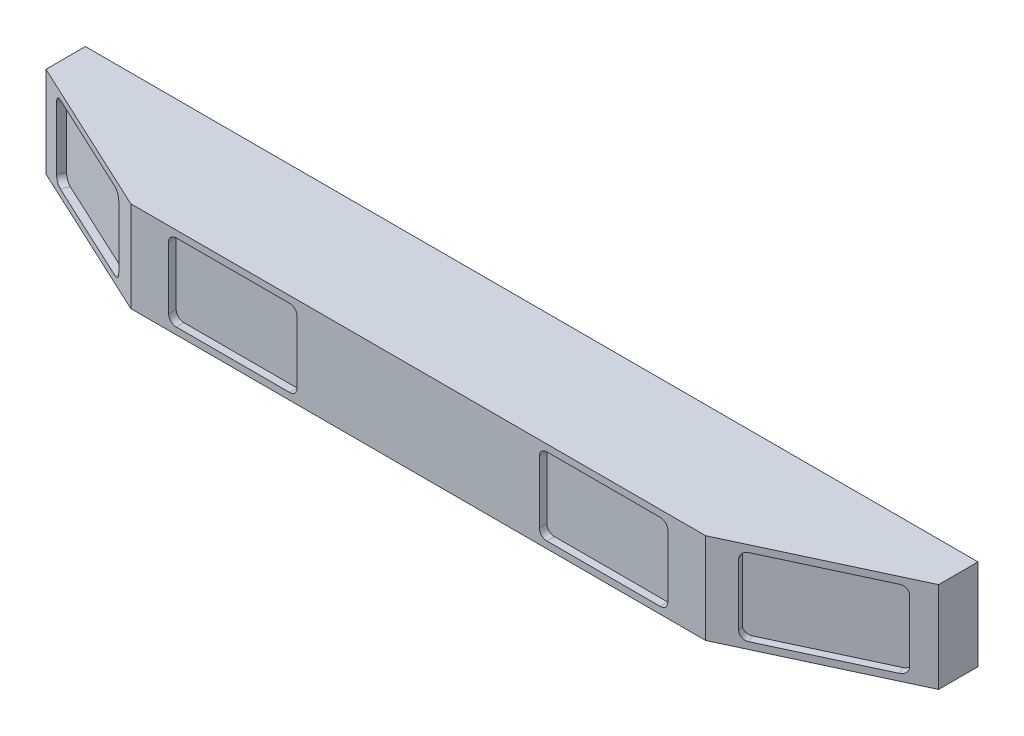
SolidWorks part; units mm, degrees
material "Stainless Steel 2205"
ref_plane "Front Plane" through (0, 0, 0) normal (0, 0, 1) x (1, 0, 0)
ref_plane "Top Plane" through (0, 0, 0) normal (0, 1, 0) x (1, 0, 0)
ref_plane "Right Plane" through (0, 0, 0) normal (1, 0, 0) x (0, 0, -1)
sketch "Sketch1" plane through (0, 0, 0) normal (0, 1, 0) x (1, 0, 0)
  line L1 (-590, 0) -> (590, 0)
  line L2 (-590, 0) -> (-590, -150)
  line L3 (-590, -150) -> (590, -150)
  line L4 (590, 0) -> (590, -150)
  point P7 (0, 0)
  dimension "D1" = 590
  dimension "D2" = 590
  dimension "D3" = 150
extrude "Boss-Extrude1" add sketch "Sketch1" against normal blind 120
sketch "Sketch2" plane through (0, 0, 0) normal (0, 0, -1) x (-1, 0, 0)
  line L0 (-590, 0) -> (590, 0) construction
  circle A0 centre (-515, -60) radius 50
  circle A1 centre (515, -60) radius 50
  dimension "D1" = 100
  dimension "D4" = 100
  dimension "D2" = 515
  dimension "D3" = 515
  dimension "D5" = 60
  dimension "D6" = 60
extrude "Cut-Extrude1" cut sketch "Sketch2" against normal blind 50
chamfer "Chamfer1" distance 210 angle 25 2 edges at (590, -60, 150) (-590, -60, 150)
sketch "Sketch3" plane through (-125.3237, 0, 268.7575) normal (-0.4226, 0, 0.9063) x (0.9063, 0, 0.4226)
  line L1 (-483.8586, -9) -> (-313.8586, -9)
  line L2 (-483.8586, -9) -> (-483.8586, -111)
  line L3 (-483.8586, -111) -> (-313.8586, -111)
  line L4 (-313.8586, -9) -> (-313.8586, -111)
  line L5 (-512.7136, -120) -> (-512.7136, 0) construction
  line L7 (-281.0042, -120) -> (-512.7136, -120) construction
  dimension "D1" = 102
  dimension "D2" = 170
  dimension "D3" = 28.855
  dimension "D4" = 9
extrude "Cut-Extrude2" cut sketch "Sketch3" against normal blind 10
fillet "Fillet2" radius 10 4 edges at (-407.6631, -9, 131.5836) (-407.6631, -111, 131.5836) (-561.7354, -111, 59.7385) (-561.7354, -9, 59.7385)
mirror "Mirror1" about plane through (0, 0, 0) normal (1, 0, 0) of "Cut-Extrude2"
sketch "Sketch4" plane through (0, 0, 150) normal (0, 0, 1) x (1, 0, 0)
  line L0 (-380, -120) -> (380, -120) construction
  line L1 (-330, -9) -> (-160, -9)
  line L2 (-330, -9) -> (-330, -111)
  line L3 (-330, -111) -> (-160, -111)
  line L4 (-160, -9) -> (-160, -111)
  line L5 (-380, 0) -> (-380, -120) construction
  dimension "D1" = 102
  dimension "D2" = 9
  dimension "D3" = 170
  dimension "D4" = 50
extrude "Cut-Extrude3" cut sketch "Sketch4" against normal blind 10
fillet "Fillet3" radius 10 4 edges at (-160, -111, 145) (-330, -111, 145) (-160, -9, 145) (-330, -9, 145)
mirror "Mirror2" about plane through (0, 0, 0) normal (1, 0, 0) of "Cut-Extrude3"
fillet "Fillet4" radius 10 8 edges at (407.6631, -111, 131.5836) (561.7354, -111, 59.7385) (561.7354, -9, 59.7385) (407.6631, -9, 131.5836) (330, -9, 145) (330, -111, 145) (160, -111, 145) (160, -9, 145)
